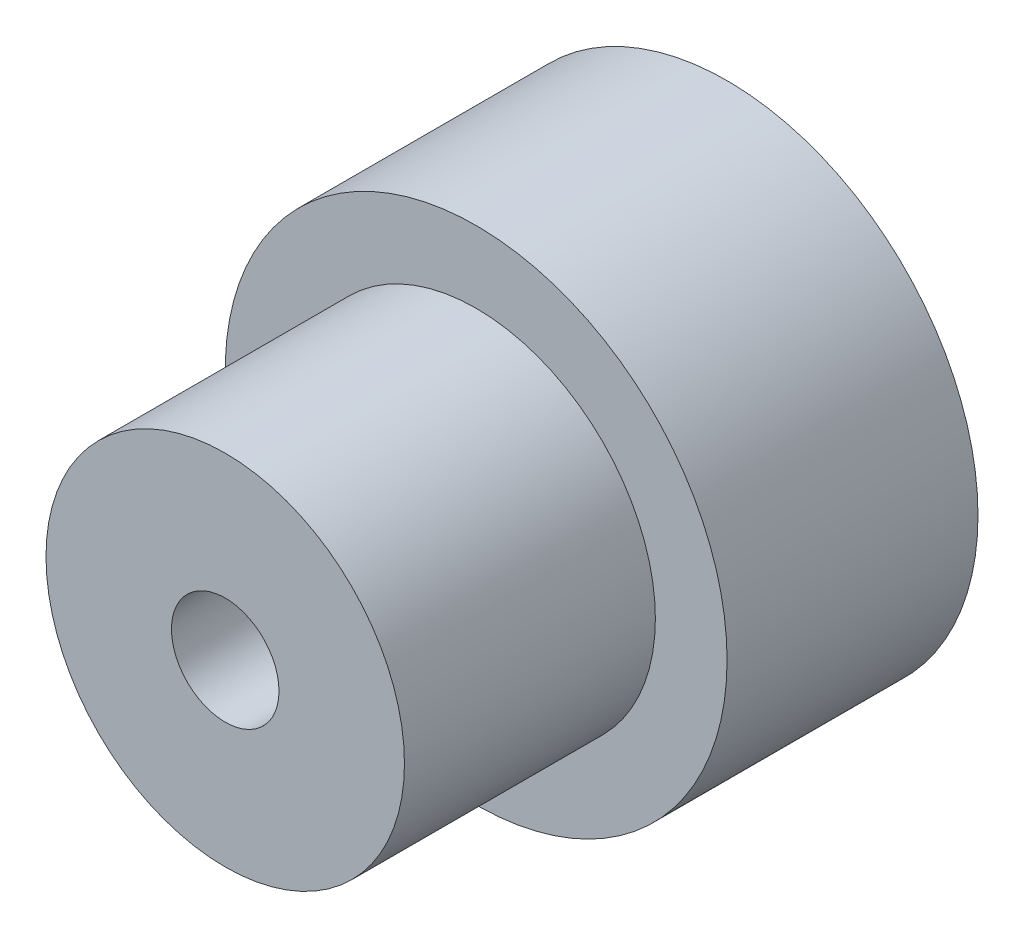
SolidWorks part; units mm, degrees
ref_plane "前视基准面" through (0, 0, 0) normal (0, 0, 1) x (1, 0, 0)
ref_plane "上视基准面" through (0, 0, 0) normal (0, 1, 0) x (1, 0, 0)
ref_plane "右视基准面" through (0, 0, 0) normal (1, 0, 0) x (0, 0, -1)
sketch "草图1" plane through (0, 0, 0) normal (0, 0, 1) x (1, 0, 0)
  circle A0 centre (0, 0) radius 7
  dimension "D1" = 14
extrude "凸台-拉伸1" add sketch "草图1" along normal blind 7
sketch "草图2" plane through (0, 0, 7) normal (0, 0, 1) x (1, 0, 0)
  circle A0 centre (0, 0) radius 5
  dimension "D1" = 10
extrude "凸台-拉伸2" add sketch "草图2" along normal blind 7
sketch "草图3" plane through (0, 0, 14) normal (0, 0, 1) x (1, 0, 0)
  circle A0 centre (0, 0) radius 1.5
  dimension "D1" = 3
extrude "切除-拉伸1" cut sketch "草图3" against normal through all
